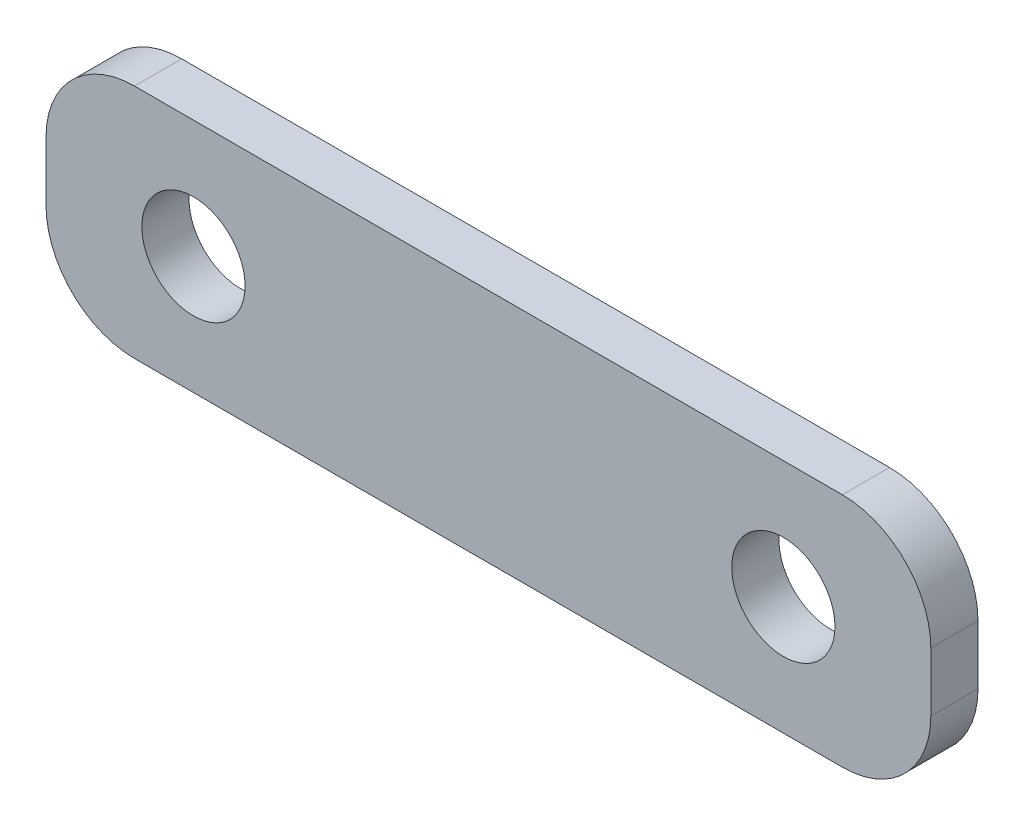
SolidWorks part; units mm, degrees
ref_plane "Plano frontal" through (0, 0, 0) normal (0, 0, 1) x (1, 0, 0)
ref_plane "Plano superior" through (0, 0, 0) normal (0, 1, 0) x (1, 0, 0)
ref_plane "Plano direito" through (0, 0, 0) normal (1, 0, 0) x (0, 0, -1)
sketch "Esboço1" plane through (0, 0, 0) normal (0, 0, 1) x (1, 0, 0)
  line L0 (0, 0) -> (0, 40)
  line L1 (0, 40) -> (150, 40)
  line L2 (150, 40) -> (150, 0)
  line L3 (150, 0) -> (0, 0)
  dimension "D1" = 40
  dimension "D2" = 150
extrude "Ressalto-extrusão1" add sketch "Esboço1" along normal mid plane 8
fillet "Filete2" radius 15 4 edges at (150, 0, 0) (150, 40, 0) (0, 0, 0) (0, 40, 0)
hole_wizard "Broca de rosquear para tarraxa de M201" positions "Esboço7" profile "Esboço6" hole size "M20" standard "DIN" end condition through all
sketch "Esboço7" plane through (0, 0, 4) normal (0, 0, 1) x (1, 0, 0)
  line L5 (0, 25) -> (0, 15) construction
  point P2 (25, 20)
  point P9 (125, 20)
  dimension "D1" = 100
  dimension "D2" = 25
sketch "Esboço6" plane through (25, 20, 4) normal (1, 0, 0) x (0, -1, 0)
  line L0 (0, 0) -> (0, 8)
  line L1 (0, 8) -> (8.75, 8)
  line L2 (8.75, 8) -> (8.75, 0)
  line L5 (8.75, 0) -> (0, 0)
  line L11 (0, -6.35) -> (0, 107.95) construction
  dimension "Thru Hole Dia." = 17.5
  dimension "Thru Hole Depth" = 8
